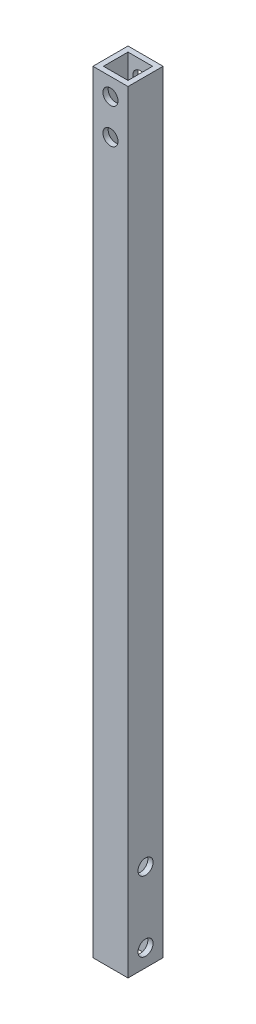
SolidWorks part; units mm, degrees
material "5052-H34"
ref_plane "正面" through (0, 0, 0) normal (0, 0, 1) x (1, 0, 0)
ref_plane "平面" through (0, 0, 0) normal (0, 1, 0) x (1, 0, 0)
ref_plane "右側面" through (0, 0, 0) normal (1, 0, 0) x (0, 0, -1)
sketch "ｽｹｯﾁ1" plane through (0, 0, 0) normal (0, 1, 0) x (1, 0, 0)
  line L1 (-5, 5) -> (5, 5)
  line L2 (-5, 5) -> (-5, -5)
  line L3 (-5, -5) -> (5, -5)
  line L4 (5, 5) -> (5, -5)
  line L5 (-5, 5) -> (5, -5) construction
  line L6 (-5, -5) -> (5, 5) construction
  point P0 (0, 0)
  dimension "D1" = 10
  dimension "D2" = 10
extrude "押し出し-薄板1" add sketch "ｽｹｯﾁ1" along normal blind 220 thin
sketch "ｽｹｯﾁ2" plane through (0, 0, 5) normal (0, 0, 1) x (1, 0, 0)
  line L0 (0, 220) -> (0, 205) construction
  line L1 (-5, 220) -> (5, 220) construction
  circle A0 centre (0, 205) radius 2.15
  circle A1 centre (0, 215) radius 2.15
  dimension "D1" = 4.3
  dimension "D2" = 5
  dimension "D3" = 10
extrude "ｶｯﾄ - 押し出し1" cut sketch "ｽｹｯﾁ2" against normal through all
sketch "ｽｹｯﾁ3" plane through (5, 0, 0) normal (1, 0, 0) x (0, 0, -1)
  line L0 (0, 5) -> (0, 0) construction
  line L2 (0, 5) -> (0, 25) construction
  circle A1 centre (0, 5) radius 2.15
  circle A2 centre (0, 25) radius 2.15
  dimension "D1" = 4.3
  dimension "D2" = 5
  dimension "D4" = 20
extrude "ｶｯﾄ - 押し出し2" cut sketch "ｽｹｯﾁ3" against normal through all
